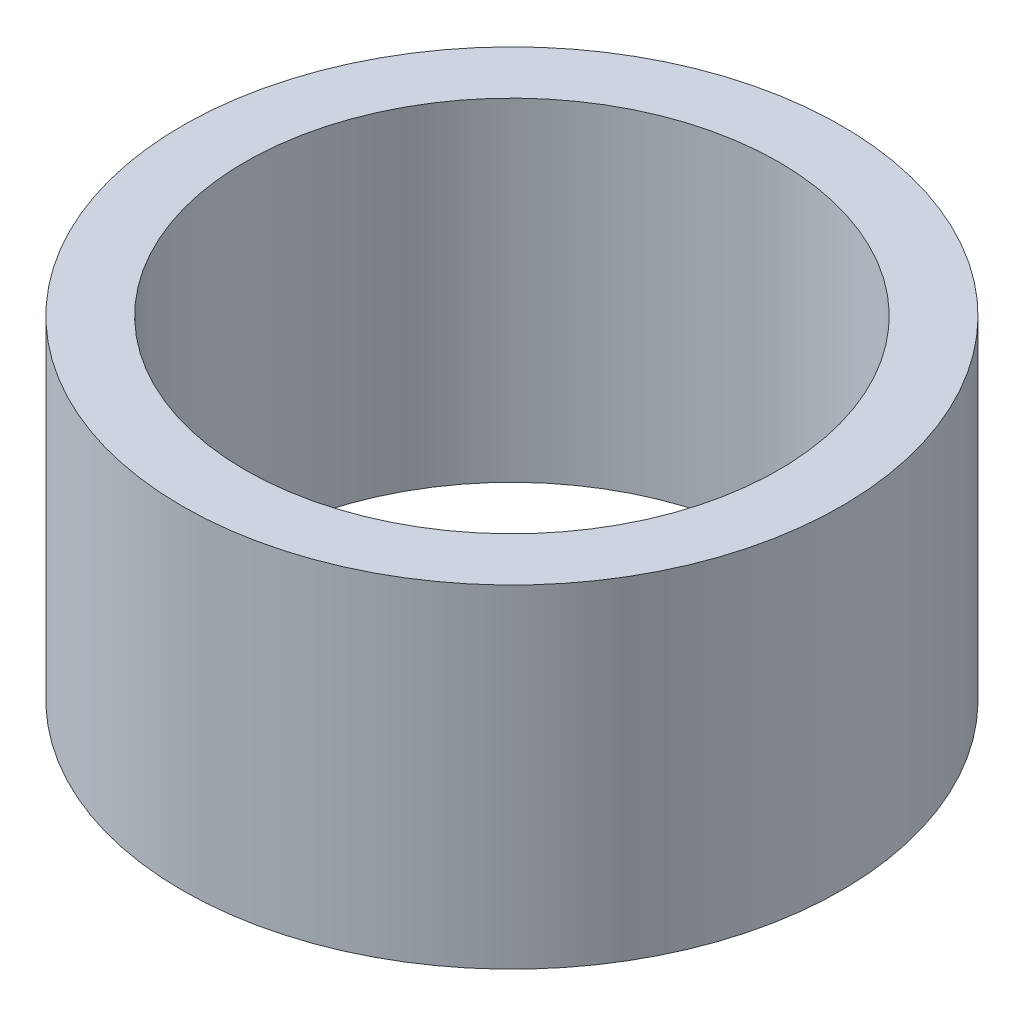
SolidWorks part; units mm, degrees
ref_plane "Plan de face" through (0, 0, 0) normal (0, 0, 1) x (1, 0, 0)
ref_plane "Plan de dessus" through (0, 0, 0) normal (0, 1, 0) x (1, 0, 0)
ref_plane "Plan de droite" through (0, 0, 0) normal (1, 0, 0) x (0, 0, -1)
sketch "Esquisse1" plane through (0, 0, 0) normal (0, 1, 0) x (1, 0, 0)
  circle A0 centre (0, 0) radius 4.25
  circle A1 centre (0, 0) radius 5.25
  dimension "D1" = 8.5
  dimension "D2" = 1
extrude "Boss.-Extru.1" add sketch "Esquisse1" along normal blind 5.3
